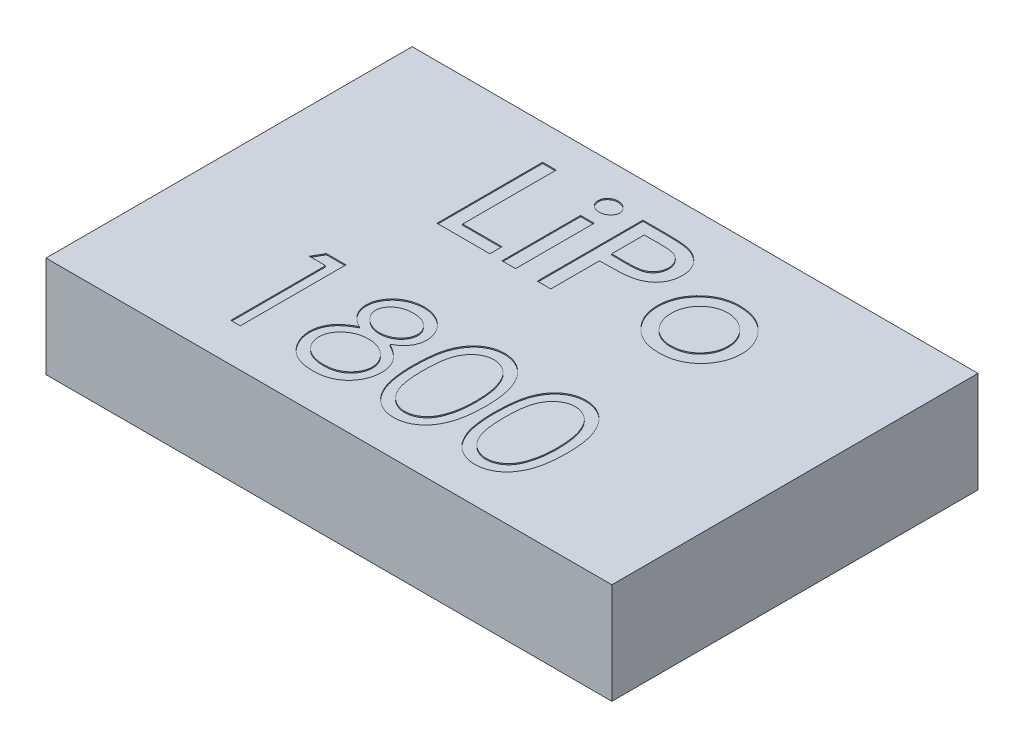
SolidWorks part; units mm, degrees
ref_plane "Front Plane" through (0, 0, 0) normal (0, 0, 1) x (1, 0, 0)
ref_plane "Top Plane" through (0, 0, 0) normal (0, 1, 0) x (1, 0, 0)
ref_plane "Right Plane" through (0, 0, 0) normal (1, 0, 0) x (0, 0, -1)
sketch "Sketch1" plane through (0, 0, 0) normal (0, 1, 0) x (1, 0, 0)
  line L1 (25.5, -16.5) -> (-25.5, -16.5)
  line L2 (25.5, -16.5) -> (25.5, 16.5)
  line L3 (25.5, 16.5) -> (-25.5, 16.5)
  line L4 (-25.5, -16.5) -> (-25.5, 16.5)
  line L5 (25.5, -16.5) -> (-25.5, 16.5) construction
  line L6 (25.5, 16.5) -> (-25.5, -16.5) construction
  point P0 (0, 0)
  dimension "D1" = 51
  dimension "D2" = 33
extrude "Boss-Extrude1" add sketch "Sketch1" along normal blind 9.1
sketch "Sketch2" plane through (0, 9.1, 0) normal (0, 1, 0) x (1, 0, 0)
  text T0 "<b> LiPo</b>\r\n1800" font "Century Gothic" height in points 36
extrude "Cut-Extrude1" cut sketch "Sketch2" against normal blind 0.1
